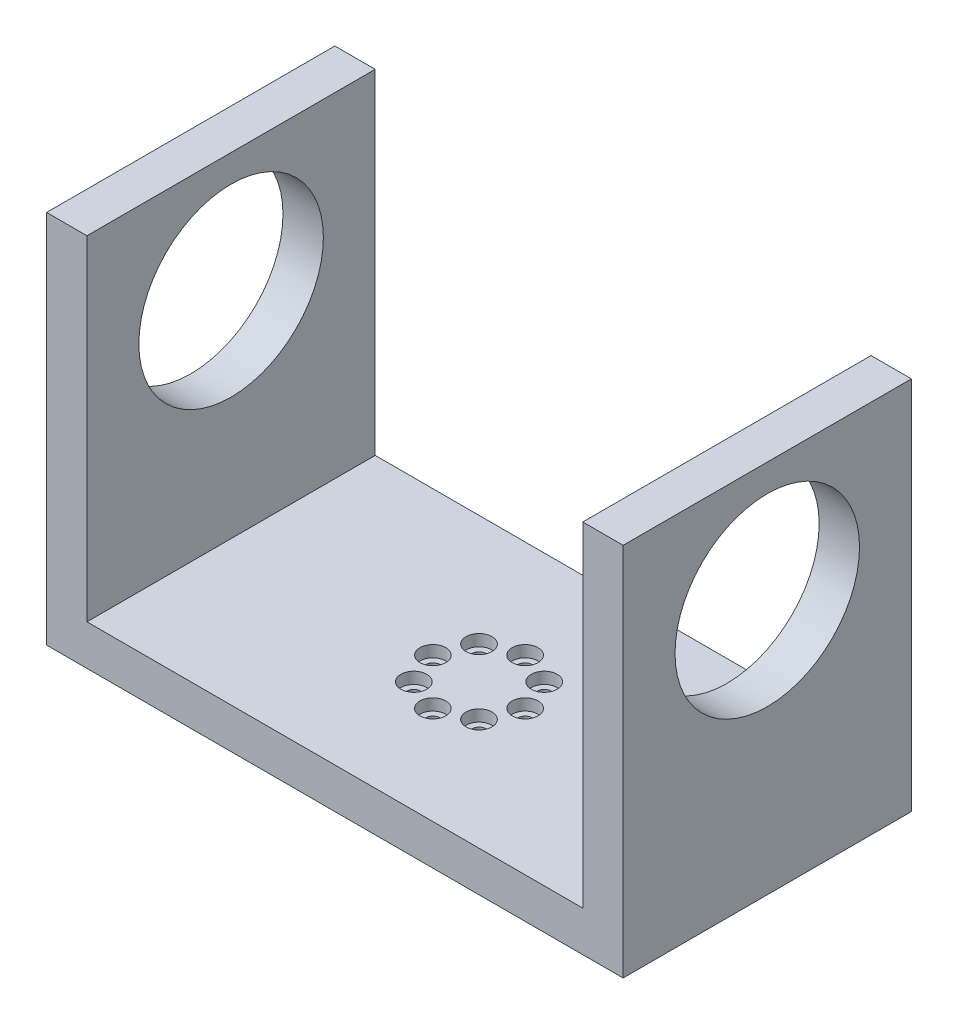
SolidWorks part; units mm, degrees
ref_plane "정면" through (0, 0, 0) normal (0, 0, 1) x (1, 0, 0)
ref_plane "윗면" through (0, 0, 0) normal (0, 1, 0) x (1, 0, 0)
ref_plane "우측면" through (0, 0, 0) normal (1, 0, 0) x (0, 0, -1)
sketch "Sketch1" plane through (0, 0, 0) normal (0, 0, 1) x (1, 0, 0)
  line L0 (0, 0) -> (0, 55.2175) construction
  line L1 (-50, 0) -> (50, 0)
  line L2 (50, 0) -> (50, 65)
  line L3 (-50, 0) -> (-50, 65)
  line L4 (50, 65) -> (43, 65)
  line L5 (-50, 65) -> (-43, 65)
  line L6 (43, 65) -> (43, 7)
  line L7 (-43, 65) -> (-43, 7)
  line L8 (43, 7) -> (-43, 7)
  point P11 (0, 7)
  dimension "D1" = 100
  dimension "D2" = 7
  dimension "D3" = 7
  dimension "D4" = 65
extrude "Boss-Extrude1" add sketch "Sketch1" along normal blind 50
sketch "Sketch3" plane through (43, 0, 0) normal (1, 0, 0) x (0, 0, -1)
  line L0 (-25, 0) -> (-25, 64.0311) construction
  line L1 (-50, 0) -> (0, 0) construction
  line L3 (-50, 7) -> (0, 7) construction
  circle A0 centre (-25, 44.25) radius 16
  dimension "D1" = 37.25
  dimension "D2" = 32
sketch "Sketch4" plane through (0, 7, 0) normal (0, -1, 0) x (1, 0, 0)
  line L0 (0, 0) -> (0, 63.9224) construction
  circle A0 centre (0, 25) radius 8 construction
  point P5 (0, 33)
  point P6 (5.6569, 30.6569)
  point P9 (8, 25)
  point P10 (5.6569, 19.3431)
  point P11 (0, 17)
  point P12 (-5.6569, 19.3431)
  point P13 (-8, 25)
  point P14 (-5.6569, 30.6569)
  point P15 (0, 25)
  dimension "D1" = 16
  dimension "D2" = 8
hole_wizard "CBORE for M2 Socket Head Cap Screw1" positions "3DSketch2" profile "Sketch6" counterbore size "M2" standard "KS" end condition through all
sketch3d "3DSketch2"
  point P0 (0, 7, 17)
  point P3 (5.6569, 7, 19.3431)
  point P6 (8, 7, 25)
  point P9 (5.6569, 7, 30.6569)
  point P12 (0, 7, 33)
  point P15 (-5.6569, 7, 30.6569)
  point P18 (-8, 7, 25)
  point P21 (-5.6569, 7, 19.3431)
sketch "Sketch6" plane through (0, 7, 17) normal (1, 0, 0) x (0, 0, 1)
  line L0 (0, 0) -> (0, 7)
  line L1 (0, 7) -> (1.2, 7)
  line L3 (1.2, 7) -> (1.2, 2)
  line L4 (1.2, 2) -> (2.25, 2)
  line L5 (2.25, 2) -> (2.25, 0)
  line L7 (2.25, 0) -> (0, 0)
  line L11 (0, -6.35) -> (0, 107.95) construction
  dimension "Thru Hole Dia." = 2.4
  dimension "Thru Hole Depth" = 7
  dimension "C'Bore Dia." = 4.5
  dimension "C'Bore Depth" = 2
sketch "Sketch7" plane through (0, 0, 0) normal (0, -1, 0) x (1, 0, 0)
  line L0 (0, 0) -> (0, 50) construction
  line L1 (-50, 0) -> (50, 0) construction
  line L2 (-50, 50) -> (50, 50) construction
  circle A0 centre (0, 25) radius 4
  dimension "D1" = 8
extrude "Cut-Extrude2" cut sketch "Sketch7" against normal blind 2.2 contours A0
sketch "Sketch8" plane through (0, 2.2, 0) normal (0, -1, 0) x (1, 0, 0)
  circle A0 centre (0, 25) radius 2.5
extrude "Cut-Extrude3" cut sketch "Sketch8" against normal blind 3
extrude "Cut-Extrude4" cut sketch "Sketch3" against normal through all and the other way through all contours A0
